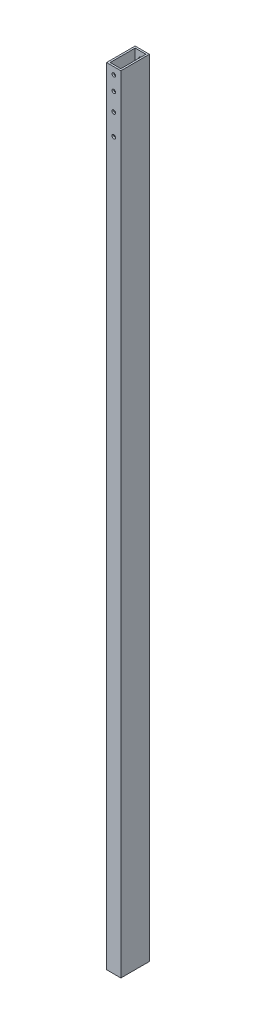
SolidWorks part; units mm, degrees
material "6061-T6 (SS)"
ref_plane "Front Plane" through (0, 0, 0) normal (0, 0, 1) x (1, 0, 0)
ref_plane "Top Plane" through (0, 0, 0) normal (0, 1, 0) x (1, 0, 0)
ref_plane "Right Plane" through (0, 0, 0) normal (1, 0, 0) x (0, 0, -1)
ref_plane "Plane1" through (0, 25.4, 0) normal (0, 1, 0) x (1, 0, 0)
sketch "Sketch1" plane through (0, 25.4, 0) normal (0, 1, 0) x (1, 0, 0)
  line L0 (292.1, 190.5) -> (292.1, 241.3) construction
  line L1 (292.1, 241.3) -> (266.7, 241.3) construction
  line L2 (266.7, 190.5) -> (266.7, 241.3) construction
  line L3 (292.1, 190.5) -> (266.7, 190.5) construction
  line L4 (292.1, 190.5) -> (292.1, 241.3)
  line L5 (292.1, 241.3) -> (266.7, 241.3)
  line L6 (266.7, 190.5) -> (266.7, 241.3)
  line L7 (292.1, 190.5) -> (266.7, 190.5)
  line L8 (288.925, 193.675) -> (288.925, 238.125)
  line L9 (288.925, 238.125) -> (269.875, 238.125)
  line L10 (269.875, 193.675) -> (269.875, 238.125)
  line L11 (288.925, 193.675) -> (269.875, 193.675)
  dimension "D1" = 3.175
extrude "Boss-Extrude1" add sketch "Sketch1" along normal up to vertex (1397 mm away)
sketch "Sketch2" plane through (0, 0, 0) normal (0, 0, 1) x (1, 0, 0)
  circle A0 centre (279.4, 1314.45) radius 3.2639 construction
  circle A1 centre (279.4, 1352.55) radius 3.2639 construction
  circle A2 centre (279.4, 1314.45) radius 3.2639
  circle A3 centre (279.4, 1352.55) radius 3.2639
extrude "Cut-Extrude1" cut sketch "Sketch2" against normal through all
sketch "Sketch3" plane through (0, 0, 0) normal (0, 0, 1) x (1, 0, 0)
  circle A0 centre (279.4, 1384.3) radius 3.175 construction
  circle A1 centre (279.4, 1409.7) radius 3.175 construction
  circle A2 centre (279.4, 1384.3) radius 3.175
  circle A3 centre (279.4, 1409.7) radius 3.175
extrude "Cut-Extrude2" cut sketch "Sketch3" against normal through all and the other way through all
sketch "Sketch4" plane through (292.1, 0, 0) normal (1, 0, 0) x (0, 0, -1)
  line L0 (215.9, 639.314) -> (215.9, 690.114) construction
  line L1 (206.375, 639.314) -> (206.375, 690.114)
  line L2 (225.425, 639.314) -> (225.425, 690.114)
  line L3 (190.5, 25.4) -> (241.3, 25.4) construction
  line L4 (190.5, 617.089) -> (241.3, 617.089) construction
  line L7 (215.9, 639.314) -> (215.9, 617.089) construction
  arc A0 (206.375, 639.314) -> (225.425, 639.314) centre (215.9, 639.314) ccw
  arc A1 (225.425, 690.114) -> (206.375, 690.114) centre (215.9, 690.114) ccw
  point P2 (215.9, 664.714)
  point P7 (0, 0)
  point P10 (215.9, 25.4)
  point P11 (215.9, 617.089)
  dimension "D2" = 9.525
  dimension "D1" = 50.8
  dimension "D3" = 22.225
extrude "Cut-Extrude3" [suppressed] cut sketch "Sketch4" against normal through all
pattern_linear "LPattern1" [suppressed] count 16 spacing 88.9
